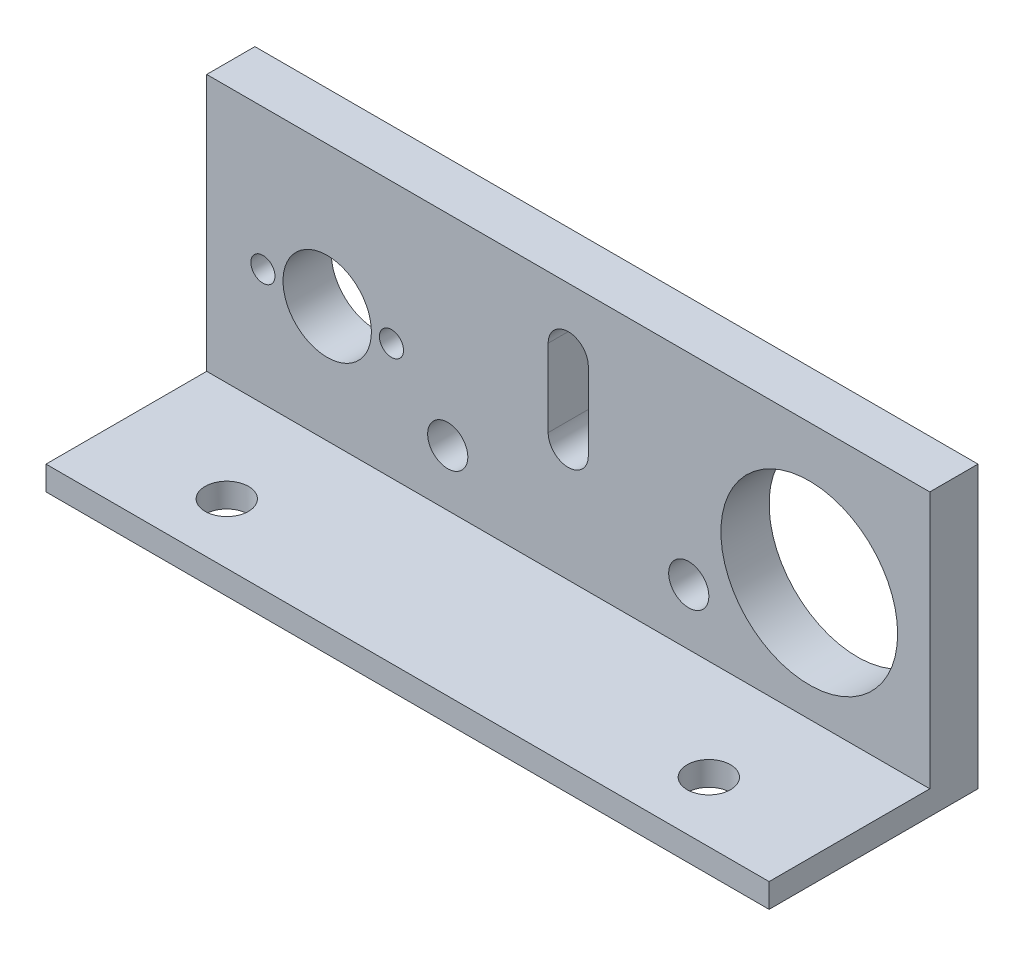
SolidWorks part; units mm, degrees
ref_plane "Front Plane" through (0, 0, 0) normal (0, 0, 1) x (1, 0, 0)
ref_plane "Top Plane" through (0, 0, 0) normal (0, 1, 0) x (1, 0, 0)
ref_plane "Right Plane" through (0, 0, 0) normal (1, 0, 0) x (0, 0, -1)
sketch "Sketch1" plane through (0, 0, 0) normal (0, 0, 1) x (1, 0, 0)
  line L1 (-45, -17.5) -> (45, -17.5)
  line L2 (-45, -17.5) -> (-45, 17.5)
  line L3 (-45, 17.5) -> (45, 17.5)
  line L4 (45, -17.5) -> (45, 17.5)
  line L5 (-45, -17.5) -> (45, 17.5) construction
  line L6 (-45, 17.5) -> (45, -17.5) construction
  circle A0 centre (-30, 0) radius 5.5
  circle A1 centre (-38, 0) radius 1.5
  circle A2 centre (-22, 0) radius 1.5
  circle A3 centre (29.9997, 0.2) radius 11
  point P0 (0, 0)
  point P14 (0, 0)
  dimension "D3" = 11
  dimension "D4" = 3
  dimension "D5" = 3
  dimension "D11" = 22
  dimension "D1" = 90
  dimension "D2" = 35
  dimension "D6" = 16
  dimension "D7" = 8
  dimension "D8" = 17.5
  dimension "D9" = 60
  dimension "D10" = 15
  dimension "D12" = 17.3
extrude "Boss-Extrude1" add sketch "Sketch1" along normal blind 6
sketch "Sketch2" plane through (0, 0, 6) normal (0, 0, 1) x (1, 0, 0)
  line L0 (45, -17.5) -> (45, 17.5) construction
  line L1 (-45, -17.5) -> (45, -17.5)
  line L2 (-45, -17.5) -> (-45, -14.5)
  line L3 (-45, -14.5) -> (45, -14.5)
  line L4 (45, -17.5) -> (45, -14.5)
  dimension "D1" = 3
extrude "Boss-Extrude2" add sketch "Sketch2" along normal blind 20
sketch "Sketch4" plane through (0, 0, 6) normal (0, 0, 1) x (1, 0, 0)
  line L0 (0, 35.5343) -> (0, -35.2513) construction
  line L1 (0, 9.779) -> (0, 0.1415) construction
  line L2 (2.5, 9.779) -> (2.5, 0.1415)
  line L3 (-2.5, 9.779) -> (-2.5, 0.1415)
  line L5 (45, 17.5) -> (-45, 17.5) construction
  circle A0 centre (15, -7.5) radius 2.5
  arc A2 (2.5, 9.779) -> (-2.5, 9.779) centre (0, 9.779) ccw
  arc A3 (-2.5, 0.1415) -> (2.5, 0.1415) centre (0, 0.1415) ccw
  circle A4 centre (-15, -7.5) radius 2.5
  point P8 (0, 4.9603)
  dimension "D1" = 15
  dimension "D2" = 5
  dimension "D3" = 2.5
  dimension "D5" = 25
extrude "Cut-Extrude1" cut sketch "Sketch4" against normal blind 10
sketch "Sketch5" plane through (0, -14.5, 0) normal (0, 1, 0) x (1, 0, 0)
  line L2 (0, 41.8575) -> (0, -20.6725) construction
  line L3 (45, -26) -> (-45, -26) construction
  line L4 (45, -26) -> (45, -6) construction
  circle A0 centre (30, -18.5) radius 2.7
  circle A2 centre (-30, -18.5) radius 2.7
  dimension "D3" = 5.4
  dimension "D1" = 7.5
  dimension "D2" = 15
extrude "Cut-Extrude2" cut sketch "Sketch5" against normal blind 10
